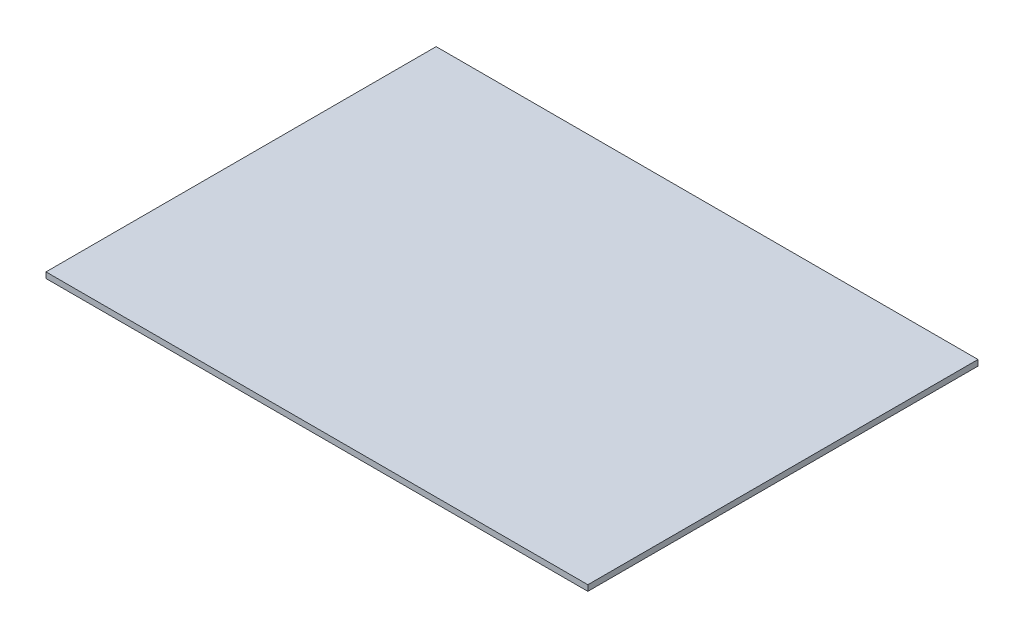
SolidWorks part; units mm, degrees
ref_plane "Plan de face" through (0, 0, 0) normal (0, 0, 1) x (1, 0, 0)
ref_plane "Plan de dessus" through (0, 0, 0) normal (0, 1, 0) x (1, 0, 0)
ref_plane "Plan de droite" through (0, 0, 0) normal (1, 0, 0) x (0, 0, -1)
sketch "Esquisse1" plane through (0, 0, 0) normal (0, 1, 0) x (1, 0, 0)
  line L1 (-75, -54) -> (75, -54)
  line L2 (-75, -54) -> (-75, 54)
  line L3 (-75, 54) -> (75, 54)
  line L4 (75, -54) -> (75, 54)
  line L5 (-75, -54) -> (75, 54) construction
  line L6 (-75, 54) -> (75, -54) construction
  point P0 (0, 0)
  dimension "D1" = 150
  dimension "D2" = 108
extrude "Boss.-Extru.1" add sketch "Esquisse1" along normal blind 1.6
